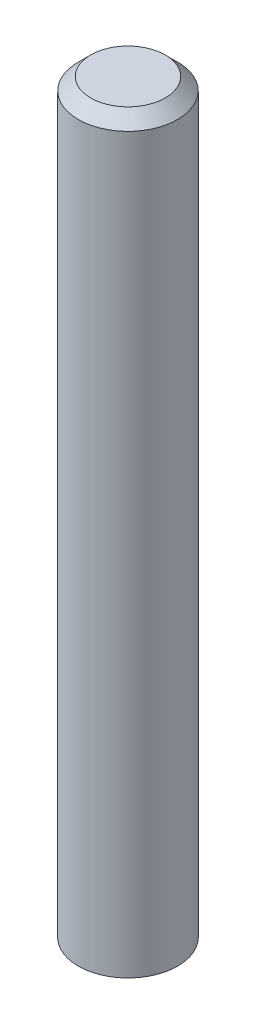
SolidWorks part; units mm, degrees
material "1023 Carbon Steel Sheet (SS)"
ref_plane "Front Plane" through (0, 0, 0) normal (0, 0, 1) x (1, 0, 0)
ref_plane "Top Plane" through (0, 0, 0) normal (0, 1, 0) x (1, 0, 0)
ref_plane "Right Plane" through (0, 0, 0) normal (1, 0, 0) x (0, 0, -1)
sketch "Sketch1" plane through (0, 0, 0) normal (0, 1, 0) x (1, 0, 0)
  circle A0 centre (0, 0) radius 4
  dimension "D1" = 8
extrude "Boss-Extrude1" add sketch "Sketch1" along normal blind 60
chamfer "Chamfer1" distance 1 angle 45 1 edges at (0, 60, 4)
